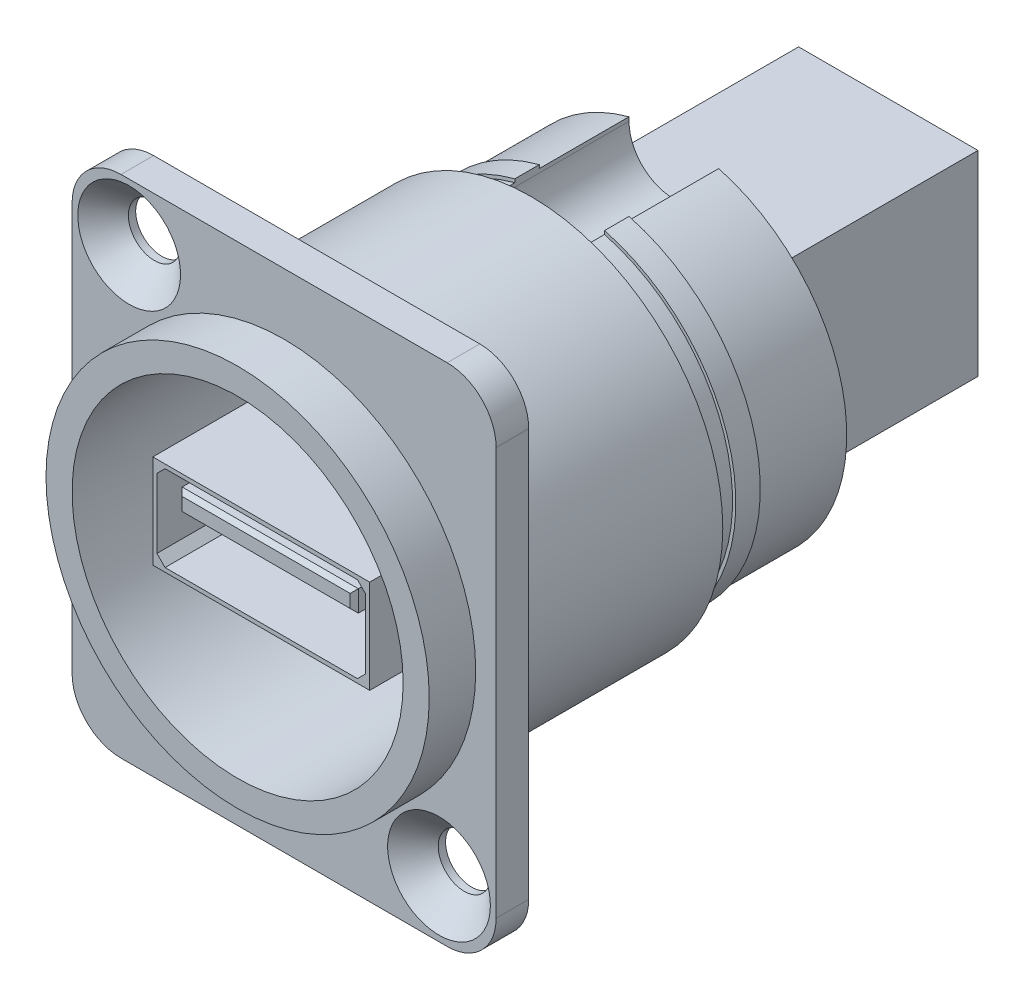
SolidWorks part; units mm, degrees
ref_plane "Front Plane" through (0, 0, 0) normal (0, 0, 1) x (1, 0, 0)
ref_plane "Top Plane" through (0, 0, 0) normal (0, 1, 0) x (1, 0, 0)
ref_plane "Right Plane" through (0, 0, 0) normal (1, 0, 0) x (0, 0, -1)
sketch "Sketch1" plane through (0, 0, 0) normal (0, 0, 1) x (1, 0, 0)
  circle A0 centre (0, 0) radius 10.8
  dimension "D1" = 21.6
extrude "Extrude1" add sketch "Sketch1" along normal mid plane 1.5
sketch "Sketch2" plane through (0, 0, 0.75) normal (0, 0, 1) x (1, 0, 0)
  circle A0 centre (0, 0) radius 10.6
  dimension "D1" = 21.2
extrude "Extrude2" add sketch "Sketch2" along normal blind 5.5
sketch "Sketch3" plane through (0, 0, -0.75) normal (0, 0, -1) x (-1, 0, 0)
  circle A0 centre (0, 0) radius 10.6
  dimension "D1" = 21.2
extrude "Extrude3" add sketch "Sketch3" along normal blind 5.5
sketch "Sketch4" plane through (0, 0, 6.25) normal (0, 0, 1) x (1, 0, 0)
  line L1 (-8, -4.5) -> (8, -4.5)
  line L2 (-8, -4.5) -> (-8, 4.5)
  line L3 (-8, 4.5) -> (8, 4.5)
  line L4 (8, -4.5) -> (8, 4.5)
  point P4 (0, -4.5)
  point P6 (8, 0)
  dimension "D1" = 9
  dimension "D2" = 16
extrude "Extrude4" add sketch "Sketch4" along normal blind 2
sketch "Sketch5" plane through (0, 0, 8.25) normal (0, 0, 1) x (1, 0, 0)
  line L0 (-8, 4.5) -> (-8, -4.5) construction
  line L1 (-6.65, 2.875) -> (6.65, 2.875)
  line L2 (-6.65, 2.875) -> (-6.65, -2.875)
  line L3 (-6.65, -2.875) -> (6.65, -2.875)
  line L4 (6.65, 2.875) -> (6.65, -2.875)
  line L6 (-8, -4.5) -> (8, -4.5) construction
  dimension "D1" = 13.3
  dimension "D2" = 5.75
  dimension "D3" = 1.35
  dimension "D4" = 1.625
extrude "Extrude5" add sketch "Sketch5" along normal blind 10.8
sketch "Sketch6" plane through (0, 0, 19.05) normal (0, 0, 1) x (1, 0, 0)
  line L0 (-6.65, -2.875) -> (6.65, -2.875) construction
  line L1 (-5.9, 2.625) -> (5.9, 2.625)
  line L2 (-6.4, 2.125) -> (-6.4, -2.125)
  line L3 (-5.9, -2.625) -> (5.9, -2.625)
  line L4 (6.4, 2.125) -> (6.4, -2.125)
  line L6 (-6.65, 2.875) -> (-6.65, -2.875) construction
  line L7 (6.65, -2.875) -> (6.65, 2.875) construction
  line L8 (-6.4, 2.125) -> (-5.9, 2.625)
  line L9 (-6.4, -2.125) -> (-5.9, -2.625)
  line L10 (5.9, -2.625) -> (6.4, -2.125)
  line L11 (5.9, 2.625) -> (6.4, 2.125)
  point P0 (-6.4, 2.625)
  point P1 (6.4, -2.625)
  point P2 (-6.4, -2.625)
  point P3 (6.4, 2.625)
  dimension "D1" = 5.25
  dimension "D2" = 0.25
  dimension "D3" = 0.25
  dimension "D4" = 0.25
extrude "Extrude6" cut sketch "Sketch6" against normal blind 10.8
sketch "Sketch7" plane through (0, 0, 8.25) normal (0, 0, 1) x (1, 0, 0)
  line L0 (5.9, 2.625) -> (-5.9, 2.625) construction
  line L1 (-5.4, 1.625) -> (5.4, 1.625)
  line L2 (-5.4, 1.625) -> (-5.4, 0.325)
  line L3 (-5.4, 0.325) -> (5.4, 0.325)
  line L4 (5.4, 1.625) -> (5.4, 0.325)
  line L5 (6.4, -2.125) -> (6.4, 2.125) construction
  line L6 (-6.4, 2.125) -> (-6.4, -2.125) construction
  dimension "D1" = 1.3
  dimension "D2" = 1
  dimension "D3" = 1
  dimension "D4" = 1
extrude "Extrude7" add sketch "Sketch7" along normal blind 10.5
chamfer "Chamfer1" distance 0.25 angle 45 4 edges at (5.4, 0.975, 18.75) (0, 0.325, 18.75) (-5.4, 0.975, 18.75) (0, 1.625, 18.75)
sketch "Sketch8" plane through (0, 0, -6.25) normal (0, 0, -1) x (-1, 0, 0)
  line L1 (-5.5, 6) -> (5.5, 6)
  line L2 (-5.5, 6) -> (-5.5, -6)
  line L3 (-5.5, -6) -> (5.5, -6)
  line L4 (5.5, 6) -> (5.5, -6)
  point P4 (5.5, 0)
  point P6 (0, 6)
  dimension "D1" = 12
  dimension "D2" = 11
extrude "Extrude8" add sketch "Sketch8" along normal blind 13.15
sketch "Sketch9" plane through (0, 0, -19.4) normal (0, 0, -1) x (-1, 0, 0)
  line L0 (-5.5, -6) -> (5.5, -6) construction
  line L1 (-2.85, 4.6) -> (2.85, 4.6)
  line L2 (-3.85, 3.6) -> (-3.85, -4.35)
  line L3 (-3.85, -4.35) -> (3.85, -4.35)
  line L4 (3.85, 3.6) -> (3.85, -4.35)
  line L5 (-5.5, 6) -> (-5.5, -6) construction
  line L6 (5.5, -6) -> (5.5, 6) construction
  line L7 (5.5, 6) -> (-5.5, 6) construction
  line L8 (-3.85, 3.6) -> (-2.85, 4.6)
  line L9 (2.85, 4.6) -> (3.85, 3.6)
  point P0 (-3.85, 4.6)
  point P3 (3.85, 4.6)
  dimension "D1" = 1.65
  dimension "D2" = 1.65
  dimension "D3" = 1.65
  dimension "D4" = 1.4
extrude "Extrude9" cut sketch "Sketch9" against normal blind 13.15
sketch "Sketch10" plane through (0, 0, -6.25) normal (0, 0, -1) x (-1, 0, 0)
  line L1 (-2.75, 1.5) -> (2.75, 1.5)
  line L2 (-2.75, 1.5) -> (-2.75, -1.5)
  line L3 (-2.75, -1.5) -> (2.75, -1.5)
  line L4 (2.75, 1.5) -> (2.75, -1.5)
  point P4 (0, -1.5)
  point P6 (2.75, 0)
  dimension "D1" = 5.5
  dimension "D2" = 3
extrude "Extrude10" add sketch "Sketch10" along normal blind 13
chamfer "Chamfer2" distance 0.25 angle 45 4 edges at (0, 1.5, -19.25) (-2.75, 0, -19.25) (0, -1.5, -19.25) (2.75, 0, -19.25)
sketch "Sketch11" plane through (0, 0, -6.25) normal (0, 0, -1) x (-1, 0, 0)
  line L0 (-2.75, 10) -> (-2.75, 10.444)
  line L1 (2.75, 10) -> (2.75, 10.444)
  line L2 (-2.75, -10.444) -> (-2.75, -10)
  line L3 (2.75, -10.444) -> (2.75, -10)
  arc A0 (-2.75, 10) -> (2.75, 10) centre (0, 10) ccw
  arc A1 (-2.75, -10) -> (2.75, -10) centre (0, -10) cw
  circle A2 centre (0, 0) radius 10.8 construction
  arc A3 (2.75, 10.444) -> (-2.75, 10.444) centre (0, 0) ccw
  arc A4 (-2.75, -10.444) -> (2.75, -10.444) centre (0, 0) ccw
  dimension "D2" = 10
  dimension "D3" = 10
  dimension "D4" = 5.5
extrude "Extrude11" cut sketch "Sketch11" against normal through all
sketch "Sketch12" plane through (0, 0, 6.25) normal (0, 0, 1) x (1, 0, 0)
  line L0 (7.3, 4.8) -> (8.3, 4.8)
  line L1 (-8.3, 4.8) -> (-7.3, 4.8)
  line L2 (-8.3, 4.8) -> (-8.3, -4.8)
  line L3 (-8.3, -4.8) -> (-7.3, -4.8)
  line L4 (8.3, 4.8) -> (8.3, -4.8)
  line L5 (-7.3, 5.25) -> (7.3, 5.25)
  line L6 (-7.3, 5.25) -> (-7.3, 4.8)
  line L7 (-7.3, -5.25) -> (7.3, -5.25)
  line L8 (7.3, 5.25) -> (7.3, 4.8)
  line L9 (7.3, -4.8) -> (8.3, -4.8)
  line L10 (-7.3, -4.8) -> (-7.3, -5.25)
  line L11 (7.3, -4.8) -> (7.3, -5.25)
  line L12 (-8, 4.5) -> (-8, -4.5) construction
  line L13 (8, -4.5) -> (8, 4.5) construction
  line L14 (8, 4.5) -> (-8, 4.5) construction
  line L15 (-8, -4.5) -> (8, -4.5) construction
  circle A0 centre (0, 0) radius 10.15
  dimension "D1" = 20.3
  dimension "D2" = 0.3
  dimension "D3" = 0.3
  dimension "D4" = 0.75
  dimension "D5" = 0.75
  dimension "D6" = 1
  dimension "D7" = 1
  dimension "D8" = 0.3
  dimension "D9" = 0.3
extrude "Extrude12" add sketch "Sketch12" along normal blind 1.25
sketch "Sketch13" plane through (0, 0, 7.5) normal (0, 0, 1) x (1, 0, 0)
  circle A0 centre (0, 0) radius 11.75
  circle A1 centre (0, 0) radius 10.15
  circle A2 centre (0, 0) radius 10.15
  dimension "D2" = 23.5
  dimension "D1" = 0
extrude "Extrude13" add sketch "Sketch13" along normal blind 13 and the other way blind 5
ref_plane "Plane1" through (0, 0, 17.65) normal (0, 0, 1) x (1, 0, 0)
sketch "Sketch14" plane through (0, 0, 17.65) normal (0, 0, 1) x (1, 0, 0)
  line L0 (-13, 15.5) -> (13, -15.5) construction
  line L1 (-13, 15.5) -> (13, 15.5)
  line L2 (-13, 15.5) -> (-13, -15.5)
  line L3 (-13, -15.5) -> (13, -15.5)
  line L4 (13, 15.5) -> (13, -15.5)
  circle A0 centre (0, 0) radius 11.75 construction
  circle A1 centre (0, 0) radius 11.75
  dimension "D1" = 26
  dimension "D2" = 31
extrude "Extrude14" add sketch "Sketch14" against normal blind 2
hole_wizard "CSK for M3 Countersunk Flat Head1" positions "Sketch16" profile "Sketch15" countersink size "M3" standard "BSI" end condition through all
sketch "Sketch16" plane through (0, 0, 17.65) normal (0, 0, 1) x (1, 0, 0)
  point P0 (-9.5, 12)
  point P1 (9.5, -12)
  dimension "D1" = 24
  dimension "D2" = 19
  dimension "D3" = 12
  dimension "D4" = 9.5
sketch "Sketch15" plane through (-9.5, 12, 17.65) normal (1, 0, 0) x (0, -1, 0)
  line L0 (0, 0) -> (0, 37.05)
  line L1 (0, 37.05) -> (1.6, 37.05)
  line L2 (1.6, 37.05) -> (1.6, 1.55)
  line L3 (1.6, 1.55) -> (3.15, 0)
  line L5 (3.15, 0) -> (0, 0)
  line L6 (-1.6, 1.55) -> (-3.15, 0) construction
  line L11 (0, -6.35) -> (0, 107.95) construction
  dimension "Thru Hole Dia." = 3.2
  dimension "Thru Hole Depth" = 37.05
  dimension "Near C'Sink Dia." = 6.3
  dimension "Near C'Sink Angle" = 90
fillet "Fillet1" radius 3 4 edges at (13, -15.5, 16.65) (-13, 15.5, 16.65) (13, 15.5, 16.65) (-13, -15.5, 16.65)
